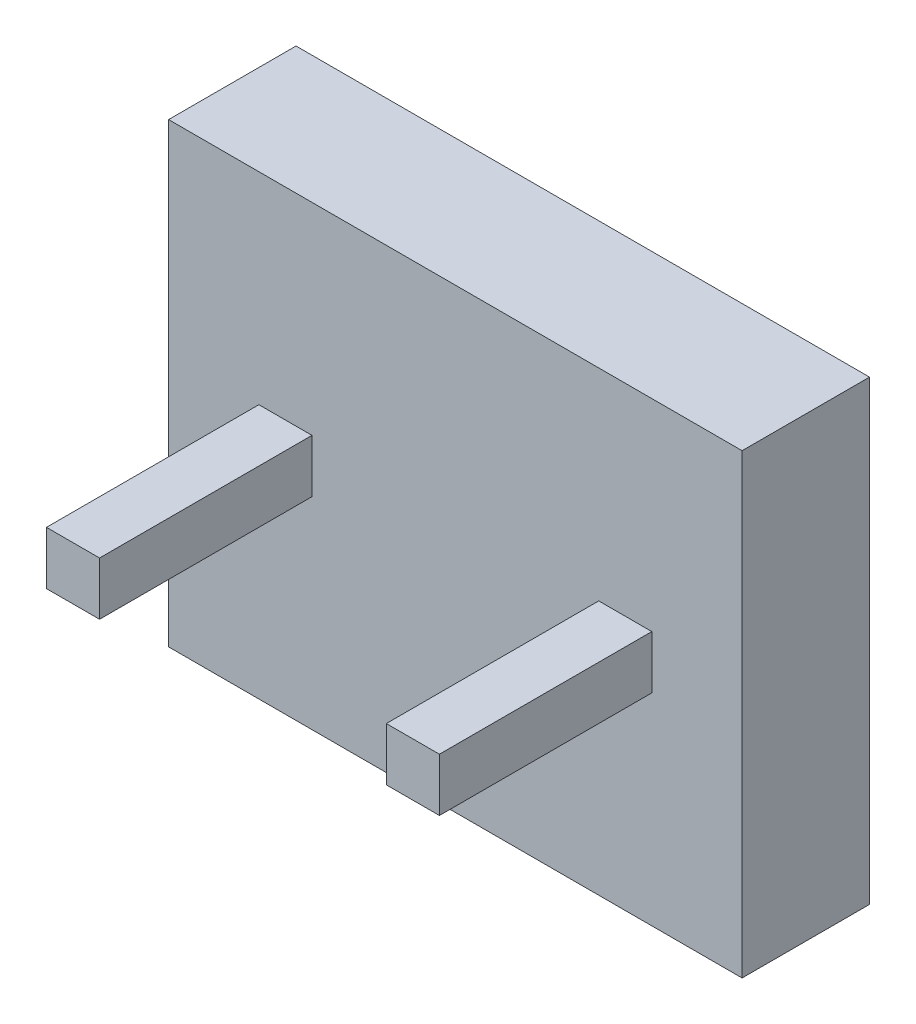
SolidWorks part; units mm, degrees
ref_plane "Front Plane" through (0, 0, 0) normal (0, 0, 1) x (1, 0, 0)
ref_plane "Top Plane" through (0, 0, 0) normal (0, 1, 0) x (1, 0, 0)
ref_plane "Right Plane" through (0, 0, 0) normal (1, 0, 0) x (0, 0, -1)
other "Configuration Table"
sketch "Sketch1" plane through (0, 0, 0) normal (0, 0, 1) x (1, 0, 0)
  line L0 (-2.7, -2.15) -> (2.7, -2.15)
  line L1 (2.7, -2.15) -> (2.7, 2.15)
  line L2 (2.7, 2.15) -> (-2.7, 2.15)
  line L3 (-2.7, 2.15) -> (-2.7, -2.15)
extrude "Body" add sketch "Sketch1" along normal blind 1.2
sketch "Sketch2" plane through (0, 0, 0) normal (0, 0, 1) x (1, 0, 0)
  line L0 (-1.85, -0.25) -> (-1.35, -0.25)
  line L1 (-1.35, -0.25) -> (-1.35, 0.25)
  line L2 (-1.35, 0.25) -> (-1.85, 0.25)
  line L3 (-1.85, 0.25) -> (-1.85, -0.25)
  line L4 (1.35, -0.25) -> (1.85, -0.25)
  line L5 (1.85, -0.25) -> (1.85, 0.25)
  line L6 (1.85, 0.25) -> (1.35, 0.25)
  line L7 (1.35, 0.25) -> (1.35, -0.25)
extrude "Leads" add sketch "Sketch2" along normal blind 2 from offset 1.2
equation "\"Jar_OD\"= 90  'ASSUMED - Part G fallback - jar outer diameter"
equation "\"Jar_H\"= 120  'ASSUMED - Part G fallback - jar height"
equation "\"Pump_L\"= 45  'ASSUMED - Part G fallback"
equation "\"Pump_W\"= 24  'ASSUMED - Part G fallback"
equation "\"Pump_H\"= 33  'ASSUMED - Part G fallback"
equation "\"Pump_Outlet_OD\"= 7.5  'ASSUMED - Part G fallback"
equation "\"Tube_OD\"= 8  'ASSUMED - Part G fallback"
equation "\"Tube_ID\"= 6  'ASSUMED - Part G fallback"
equation "\"TDS_Body_Dia\"= 12  'ASSUMED - Part G fallback"
equation "\"TDS_Wet_Len\"= 45  'ASSUMED - Part G fallback - length in water"
equation "\"DS_Tube_Dia\"= 6  'ASSUMED - Part G fallback"
equation "\"DS_Tube_Len\"= 50  'ASSUMED - Part G fallback"
equation "\"ORP_Body_Dia\"= 12  'ASSUMED - Part G fallback"
equation "\"ORP_Body_Len\"= 150  'ASSUMED - Part G fallback"
equation "\"ORP_Cap_Dia\"= 16  'ASSUMED - Part G fallback"
equation "\"Turb_W\"= 33  'ASSUMED - Part G fallback - head width"
equation "\"Turb_D\"= 28  'ASSUMED - Part G fallback - head depth"
equation "\"Turb_H\"= 30  'ASSUMED - Part G fallback - head height"
equation "\"Turb_Slot_W\"= 10  'ASSUMED - Part G fallback - slot width"
equation "\"Flow_L\"= 62  'ASSUMED - Part G fallback YF-S201"
equation "\"Flow_W\"= 36  'ASSUMED - Part G fallback"
equation "\"Flow_H\"= 35  'ASSUMED - Part G fallback"
equation "\"Thread_G12_OD\"= 20.955  'ASSUMED - Part G fallback thread G1/2 (major diameter)"
equation "\"Valve_L\"= 75  'ASSUMED - Part G fallback"
equation "\"Valve_W\"= 45  'ASSUMED - Part G fallback"
equation "\"Valve_H\"= 60  'ASSUMED - Part G fallback"
equation "\"Tee_L\"= 40  'ASSUMED - Part G fallback - overall length"
equation "\"Tee_Branch_L\"= 25  'ASSUMED - Part G fallback"
equation "\"Tee_OD\"= 12  'ASSUMED - Part G fallback"
equation "\"LED_Board_L\"= 20  'ASSUMED - Part G fallback"
equation "\"LED_Board_W\"= 20  'ASSUMED - Part G fallback - LED at centre"
equation "\"GUVA_L\"= 20  'ASSUMED - Part G fallback"
equation "\"GUVA_W\"= 12  'ASSUMED - Part G fallback - sensor at centre"
equation "\"Reed_L\"= 27  'ASSUMED - Part G fallback MC-38 half"
equation "\"Reed_W\"= 14  'ASSUMED - Part G fallback"
equation "\"Reed_H\"= 8  'ASSUMED - Part G fallback"
equation "\"ESP_L\"= 51  'ASSUMED - Part G fallback"
equation "\"ESP_W\"= 28  'ASSUMED - Part G fallback"
equation "\"TFT_L\"= 58  'ASSUMED - Part G fallback - board"
equation "\"TFT_W\"= 35  'ASSUMED - Part G fallback - board"
equation "\"TFT_Win_L\"= 35  'ASSUMED - Part G fallback - visible window"
equation "\"TFT_Win_W\"= 28  'ASSUMED - Part G fallback - visible window"
equation "\"Relay_L\"= 50  'ASSUMED - Part G fallback"
equation "\"Relay_W\"= 26  'ASSUMED - Part G fallback"
equation "\"Relay_H\"= 19  'ASSUMED - Part G fallback"
equation "\"Mosfet_L\"= 34  'ASSUMED - Part G fallback"
equation "\"Mosfet_W\"= 17  'ASSUMED - Part G fallback"
equation "\"Mosfet_H\"= 12  'ASSUMED - Part G fallback"
equation "\"TDS_Board_L\"= 42  'ASSUMED - Part G fallback"
equation "\"TDS_Board_W\"= 32  'ASSUMED - Part G fallback"
equation "\"Turb_Board_L\"= 38  'ASSUMED - Part G fallback"
equation "\"Turb_Board_W\"= 28  'ASSUMED - Part G fallback"
equation "\"BNC_Thread_Dia\"= 9.5  'ASSUMED - Part G fallback"
equation "\"Plate_L\"= 420  'ASSUMED - Part G fallback"
equation "\"Plate_W\"= 297  'ASSUMED - Part G fallback"
equation "\"Plate_T\"= 6  'ASSUMED - Part G fallback"
equation "\"Booster_L\"= 150  'ASSUMED - Part G fallback - booster pump"
equation "\"Booster_W\"= 95  'ASSUMED - Part G fallback"
equation "\"Booster_H\"= 100  'ASSUMED - Part G fallback"
equation "\"PTube_OD\"= 6.35  'ASSUMED - Part G fallback - product tube 1/4 inch"
equation "\"Qz_Out\"= 12  'ASSUMED - Part G fallback - quartz channel outside square"
equation "\"Qz_Path\"= 10  'ASSUMED - Part G fallback - quartz channel inside light path"
equation "\"Qz_L\"= 40  'ASSUMED - Part G fallback - quartz channel length"
equation "\"LED860_Dia\"= 5  'ASSUMED - Part G fallback - 860 nm LED"
equation "\"BPW_L\"= 5.4  'ASSUMED - Part G fallback - BPW34"
equation "\"BPW_W\"= 4.3  'ASSUMED - Part G fallback - BPW34"
equation "\"Cart_Dia\"= 50  'ASSUMED - Part G fallback - sediment and pre-carbon cartridges"
equation "\"Cart_L\"= 255  'ASSUMED - Part G fallback"
equation "\"UF_Dia\"= 50  'ASSUMED - Part G fallback - UF cartridge"
equation "\"UF_L\"= 260  'ASSUMED - Part G fallback"
equation "\"RO_Dia\"= 62  'ASSUMED - Part G fallback - RO membrane housing"
equation "\"RO_L\"= 300  'ASSUMED - Part G fallback"
equation "\"UVC_Dia\"= 40  'ASSUMED - Part G fallback - UV-C chamber"
equation "\"UVC_L\"= 300  'ASSUMED - Part G fallback"
equation "\"Tank_W\"= 260  'ASSUMED - Part G fallback - storage tank"
equation "\"Tank_D\"= 160  'ASSUMED - Part G fallback"
equation "\"Tank_H\"= 300  'ASSUMED - Part G fallback"
equation "\"Cab_W\"= 400  'ASSUMED - Part G fallback - purifier cabinet"
equation "\"Cab_D\"= 270  'ASSUMED - Part G fallback"
equation "\"Cab_H\"= 560  'ASSUMED - Part G fallback"
equation "\"ORP_Board_L\"= 40  'ASSUMED - Part G fallback - ORP buffer board"
equation "\"ORP_Board_W\"= 30  'ASSUMED - Part G fallback"
equation "\"Opt_Board_L\"= 50  'ASSUMED - Part G fallback - optical front-end board"
equation "\"Opt_Board_W\"= 40  'ASSUMED - Part G fallback"
equation "\"Buck_L\"= 43  'ASSUMED - Part G fallback - 12 V to 5 V buck module"
equation "\"Buck_W\"= 21  'ASSUMED - Part G fallback"
equation "\"Buck_H\"= 14  'ASSUMED - Part G fallback"
equation "\"BB_L\"= 165  'ASSUMED - Part G fallback - breadboard (As_Built_R3 only)"
equation "\"BB_W\"= 55  'ASSUMED - Part G fallback"
equation "\"BB_H\"= 10  'ASSUMED - Part G fallback"
equation "\"Cuv_W\"= 12.5  'ASSUMED - old R3 cuvette (station suppressed in SS4)"
equation "\"Cuv_D\"= 12.5  'ASSUMED - old R3 cuvette (station suppressed in SS4)"
equation "\"Cuv_H\"= 45  'ASSUMED - old R3 cuvette (station suppressed in SS4)"
equation "\"Probe_Clr\"= 0.3  'DESIGN VALUE - Part C rule 3 - printed probe hole = diameter + 0.3"
equation "\"Label_H\"= 0.6  'DESIGN VALUE - Part D - raised label height"
